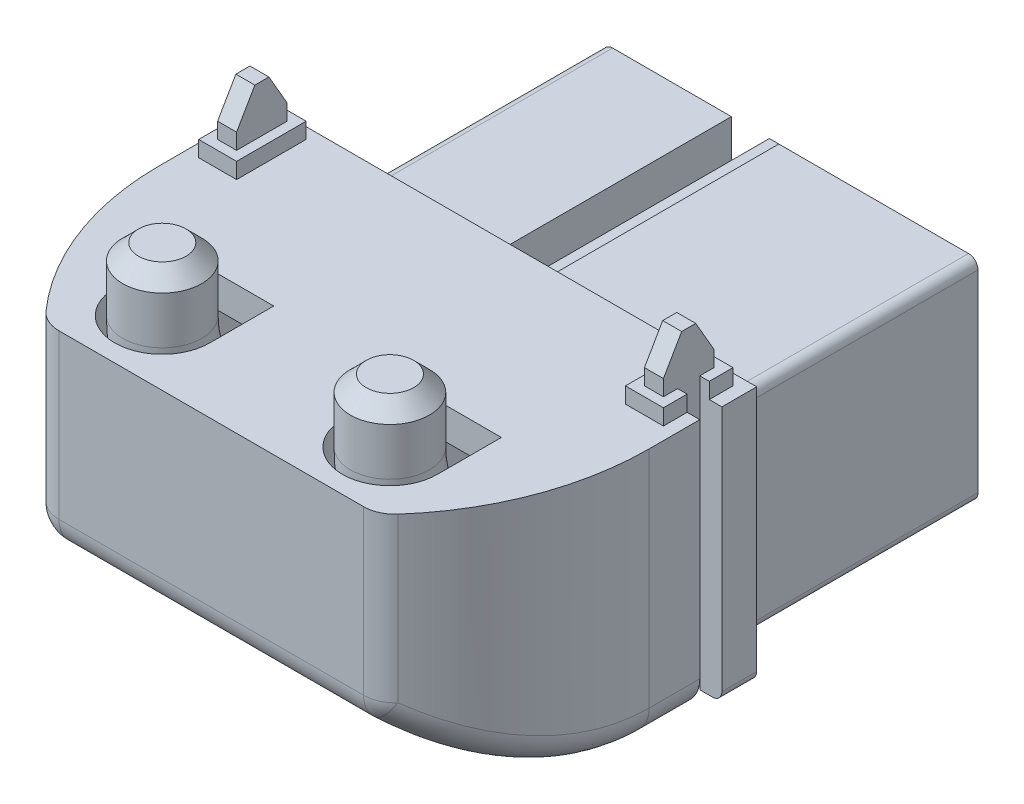
SolidWorks part; units mm, degrees
ref_plane "Спереди" through (0, 0, 0) normal (0, 0, 1) x (1, 0, 0)
ref_plane "Сверху" through (0, 0, 0) normal (0, 1, 0) x (1, 0, 0)
ref_plane "Справа" through (0, 0, 0) normal (1, 0, 0) x (0, 0, -1)
sketch "Эскиз1" plane through (0, 0, 0) normal (0, 0, 1) x (1, 0, 0)
  line L0 (-7.75, -1.2216) -> (-4.9216, -4.05)
  line L1 (-7.75, 4.05) -> (7.75, 4.05)
  line L2 (-7.75, 4.05) -> (-7.75, -4.05)
  line L3 (-7.75, -4.05) -> (7.75, -4.05)
  line L4 (7.75, 4.05) -> (7.75, -4.05)
  line L5 (-7.75, 4.05) -> (7.75, -4.05) construction
  line L6 (-7.75, -4.05) -> (7.75, 4.05) construction
  line L7 (0, 0) -> (7.75, 0) construction
  line L8 (-7.75, 1.2216) -> (-4.9216, 4.05)
  point P0 (0, 0)
  dimension "D1" = 8.1
  dimension "D2" = 15.5
  dimension "D3" = 45
  dimension "D4" = 4
extrude "Бобышка-Вытянуть1" add sketch "Эскиз1" along normal blind 11.1 contours L8 L2 L0 L3 L4 L1
sketch "Эскиз2" plane through (0, 0, 0) normal (0, 0, -1) x (-1, 0, 0)
  line L6 (7.05, 0.9316) -> (4.6316, 3.35)
  line L7 (7.05, 0.9316) -> (4.6316, 3.35)
  line L8 (4.6316, -3.35) -> (7.05, -0.9316)
  line L9 (4.6316, -3.35) -> (7.05, -0.9316)
  line L12 (-7.05, -3.35) -> (4.6316, -3.35)
  line L13 (7.05, -0.9316) -> (7.05, 0.9316)
  line L14 (4.6316, 3.35) -> (-7.05, 3.35)
  line L16 (-7.05, 3.35) -> (-7.05, -3.35)
  line L18 (-7.05, -3.35) -> (4.6316, -3.35)
  line L19 (7.05, -0.9316) -> (7.05, 0.9316)
  line L20 (4.6316, 3.35) -> (-7.05, 3.35)
  line L22 (-7.05, 3.35) -> (-7.05, -3.35)
  dimension "D1" = 0.7
extrude "Вырез-Вытянуть1" cut sketch "Эскиз2" against normal blind 7.7
sketch "Эскиз13" plane through (0, 0, 0) normal (0, 0, -1) x (-1, 0, 0)
  line L0 (0, 0) -> (0, 1.988) construction
  circle A0 centre (-3.6, 0) radius 2.175
  circle A1 centre (3.6, 0) radius 2.175
  dimension "D1" = 4.35
  dimension "D2" = 7.2
extrude "Вырез-Вытянуть9" cut sketch "Эскиз13" against normal blind 7.7
ref_plane "Плоскость1" through (0, 0, 1.5) normal (0, 0, -1) x (-1, 0, 0)
sketch "Эскиз3" plane through (0, 0, 1.5) normal (0, 0, -1) x (-1, 0, 0)
  line L1 (-7.05, 3.35) -> (4.6316, 3.35) construction
  line L2 (-0.75, 2.15) -> (0.75, 2.15)
  line L3 (-0.75, 2.15) -> (-0.75, 3.35)
  line L4 (-0.75, 3.35) -> (0.75, 3.35)
  line L5 (0.75, 2.15) -> (0.75, 3.35)
  line L6 (-0.75, 2.15) -> (0.75, 3.35) construction
  line L7 (-0.75, 3.35) -> (0.75, 2.15) construction
  point P1 (0, 2.75)
  dimension "D1" = 1.2
  dimension "D2" = 1.5
extrude "Вырез-Вытянуть10" cut sketch "Эскиз3" against normal up to surface and the other way up to surface up to face at (-1.5439, 0, 7.7) other way up to face at (1.425, 0, 0)
sketch "Эскиз14" plane through (0, 0, 0) normal (0, 0, -1) x (-1, 0, 0)
  line L1 (-0.75, 2.15) -> (0.75, 2.15)
  line L2 (-0.75, 2.15) -> (-0.75, -1.85)
  line L3 (-0.75, -1.85) -> (0.75, -1.85)
  line L4 (0.75, 2.15) -> (0.75, -1.85)
  dimension "D1" = 4
  dimension "D2" = 1.5
extrude "Бобышка-Вытянуть5" add sketch "Эскиз14" along normal blind 1.2
sketch "Эскиз5" plane through (0, 0, 7.7) normal (0, 0, -1) x (-1, 0, 0)
  line L0 (0, 0) -> (0, -2.5029) construction
  circle A0 centre (3.6, 0) radius 2.175
  circle A1 centre (-3.6, 0) radius 2.175
  dimension "D1" = 4.35
  dimension "D2" = 7.2
extrude "Бобышка-Вытянуть3" add sketch "Эскиз5" along normal offset from surface (6.5 mm away) 1.2 up to face at (-1.425, 0, 0)
sketch "Эскиз10" plane through (0, 0, 1.2) normal (0, 0, -1) x (-1, 0, 0)
  line L0 (0, 0) -> (0, 1.4291) construction
  circle A8 centre (-3.6, 0) radius 2.15
  circle A9 centre (3.6, 0) radius 2.15
  dimension "D1" = 4.3
extrude "Вырез-Вытянуть7" cut sketch "Эскиз10" against normal up to surface (6.5 mm away) up to face at (-0.9263, 1.1, 7.7)
sketch "Эскиз16" plane through (0, 0, 11.1) normal (0, 0, 1) x (1, 0, 0)
  line L0 (0, 0) -> (0, -1.8762) construction
  circle A0 centre (3.6, 0) radius 1.25
  circle A1 centre (-3.6, 0) radius 1.25
  dimension "D1" = 2.5
  dimension "D2" = 7.2
sketch "Эскиз17" plane through (0, 0, 0) normal (1, 0, 0) x (0, 0, -1)
  line L0 (-11.1, 0) -> (-11.1, 4.05) construction
  line L2 (-11.1, 4.05) -> (-15.15, 4.05) construction
  arc A0 (-15.15, 4.05) -> (-11.1, 0) centre (-11.1, 4.05) ccw
  point P7 (-11.1, 4.05)
  point P9 (-10.9589, 0)
  dimension "D1" = 4.05
sweep "По траектории1" add profiles "Эскиз16" path "Эскиз17"
sketch "Эскиз18" plane through (0, 4.05, 0) normal (0, 1, 0) x (1, 0, 0)
  circle A0 centre (3.6, -15.15) radius 1.25 construction
  circle A1 centre (-3.6, -15.15) radius 1.25 construction
  circle A2 centre (3.6, -15.15) radius 1.25
  circle A3 centre (-3.6, -15.15) radius 1.25
extrude "Бобышка-Вытянуть7" add sketch "Эскиз18" along normal blind 2
sketch "Эскиз19" plane through (0, 4.05, 0) normal (0, 1, 0) x (1, 0, 0)
  line L0 (-4.9216, -11.1) -> (7.75, -11.1) construction
  line L1 (7.75, -11.1) -> (-7.75, -11.1)
  line L2 (7.75, -11.1) -> (7.75, -17.2)
  line L3 (7.75, -17.2) -> (-7.75, -17.2)
  line L4 (-7.75, -11.1) -> (-7.75, -17.2)
  line L6 (-4.6316, 0) -> (-0.75, 0) construction
  line L7 (7.75, -11.1) -> (7.75, -7.7) construction
  line L8 (0, -17.2) -> (0, -8.2437) construction
  line L9 (5.1, -15.15) -> (5.1, -11.1)
  line L10 (2.1, -15.15) -> (2.1, -11.1)
  line L11 (-2.1, -15.15) -> (-2.1, -11.1)
  line L12 (-5.1, -15.15) -> (-5.1, -11.1)
  line L13 (7.75, -7.7) -> (-7.75, -7.7)
  line L14 (7.75, -7.7) -> (7.75, -11.1)
  line L15 (7.75, -11.1) -> (-7.75, -11.1)
  line L16 (-7.75, -7.7) -> (-7.75, -11.1)
  arc A0 (7.75, -11.1) -> (5.25, -17.2) centre (-0.942, -11.1) cw
  arc A1 (-7.75, -11.1) -> (-5.25, -17.2) centre (0.942, -11.1) ccw
  arc A2 (2.1, -15.15) -> (5.1, -15.15) centre (3.6, -15.15) ccw
  arc A3 (-2.1, -15.15) -> (-5.1, -15.15) centre (-3.6, -15.15) cw
  point P12 (-7.75, -11.1)
  dimension "D2" = 2.5
  dimension "D3" = 3
  dimension "D1" = 17.2
extrude "Бобышка-Вытянуть8" add sketch "Эскиз19" against normal up to surface (8.1 mm away) up to face at (1.4142, -4.05, 9.4)
sketch "Эскиз20" plane through (0, -4.05, 0) normal (0, -1, 0) x (1, 0, 0)
  line L4 (-7.75, 7.7) -> (7.75, 7.7)
  line L5 (7.75, 7.7) -> (7.75, 11.1)
  line L6 (5.25, 17.2) -> (-5.25, 17.2)
  line L7 (-7.75, 11.1) -> (-7.75, 7.7)
  line L8 (-7.75, 7.7) -> (7.75, 7.7)
  line L9 (7.75, 7.7) -> (7.75, 11.1)
  line L10 (5.25, 17.2) -> (-5.25, 17.2)
  line L12 (-7.75, 11.1) -> (-7.75, 7.7)
  arc A2 (7.75, 11.1) -> (5.25, 17.2) centre (-0.942, 11.1) ccw
  arc A3 (-5.25, 17.2) -> (-7.75, 11.1) centre (0.942, 11.1) ccw
  arc A4 (7.75, 11.1) -> (5.25, 17.2) centre (-0.942, 11.1) ccw
  arc A5 (-5.25, 17.2) -> (-7.75, 11.1) centre (0.942, 11.1) ccw
  dimension "D1" = 0
extrude "Бобышка-Вытянуть9" add sketch "Эскиз20" against normal blind 2.1
sketch "Эскиз21" plane through (0, 4.05, 0) normal (0, 1, 0) x (1, 0, 0)
  line L0 (-5.1, -15.15) -> (-5.1, -11.1) construction
  line L1 (5.1, -11.1) -> (-5.1, -11.1)
  line L2 (5.1, -11.1) -> (5.1, -13.125)
  line L3 (5.1, -13.125) -> (-5.1, -13.125)
  line L4 (-5.1, -11.1) -> (-5.1, -13.125)
extrude "Бобышка-Вытянуть12" add sketch "Эскиз21" against normal blind 1
sketch "Эскиз22" plane through (0, 4.05, 0) normal (0, 1, 0) x (1, 0, 0)
  line L0 (0, -9.1897) -> (0, 0) construction
  line L1 (-7.05, -8.35) -> (-6.45, -8.35)
  line L2 (-7.05, -8.35) -> (-7.05, -9.95)
  line L3 (-7.05, -9.95) -> (-6.45, -9.95)
  line L4 (-6.45, -8.35) -> (-6.45, -9.95)
  line L5 (-7.05, -8.35) -> (-6.45, -9.95) construction
  line L6 (-7.05, -9.95) -> (-6.45, -8.35) construction
  line L11 (7.05, -9.95) -> (6.45, -8.35) construction
  line L12 (7.05, -8.35) -> (6.45, -9.95) construction
  line L13 (6.45, -8.35) -> (6.45, -9.95)
  line L14 (7.05, -9.95) -> (6.45, -9.95)
  line L15 (7.05, -8.35) -> (7.05, -9.95)
  line L16 (7.05, -8.35) -> (6.45, -8.35)
  point P0 (-6.75, -9.15)
  point P12 (-3.6, -15.15)
  point P13 (6.75, -9.15)
  dimension "D1" = 1.6
  dimension "D2" = 0.6
  dimension "D3" = 6
  dimension "D4" = 13.5
extrude "Вырез-Вытянуть12" cut sketch "Эскиз22" against normal through all
sketch "Эскиз23" plane through (0, 4.05, 0) normal (0, 1, 0) x (1, 0, 0)
  line L0 (-7.05, -9.15) -> (7.05, -9.15) construction
  line L1 (-7.05, -8.35) -> (-7.05, -9.95) construction
  line L2 (7.05, -9.95) -> (7.05, -8.35) construction
  line L3 (-7.75, -11.1) -> (-7.75, -7.7) construction
  line L4 (-7.75, -8.8) -> (-7.05, -8.8)
  line L5 (-7.75, -8.8) -> (-7.75, -9.5)
  line L6 (-7.75, -9.5) -> (-7.05, -9.5)
  line L7 (-7.05, -8.8) -> (-7.05, -9.5)
  line L8 (-7.75, -8.8) -> (-7.05, -9.5) construction
  line L9 (-7.75, -9.5) -> (-7.05, -8.8) construction
  line L10 (0, 0) -> (0, -11.1203) construction
  line L11 (7.75, -9.5) -> (7.05, -9.5)
  line L12 (7.05, -8.8) -> (7.05, -9.5)
  line L13 (7.75, -8.8) -> (7.05, -8.8)
  line L14 (7.75, -8.8) -> (7.75, -9.5)
  point P6 (-7.4, -9.15)
  dimension "D1" = 0.7
extrude "Вырез-Вытянуть13" cut sketch "Эскиз23" against normal through all
sketch "Эскиз24" plane through (0, 4.05, 0) normal (0, 1, 0) x (1, 0, 0)
  line L1 (-7.05, -8.35) -> (-6.45, -8.35)
  line L2 (-7.05, -8.35) -> (-7.05, -9.95)
  line L3 (-7.05, -9.95) -> (-6.45, -9.95)
  line L4 (-6.45, -8.35) -> (-6.45, -9.95)
  line L5 (6.45, -8.35) -> (7.05, -8.35)
  line L6 (6.45, -8.35) -> (6.45, -9.95)
  line L7 (6.45, -9.95) -> (7.05, -9.95)
  line L8 (7.05, -8.35) -> (7.05, -9.95)
extrude "Бобышка-Вытянуть13" add sketch "Эскиз24" along normal blind 2 and the other way offset from surface (7.6 mm away) 0.5 other way up to face at (0, -4.05, 9.9497)
sketch "Эскиз25" plane through (0, 4.05, 0) normal (0, 1, 0) x (1, 0, 0)
  line L0 (-7.05, -8.35) -> (-7.05, -8.8) construction
  line L1 (-7.35, -8.05) -> (-6.15, -8.05)
  line L2 (-7.35, -8.05) -> (-7.35, -10.25)
  line L3 (-7.35, -10.25) -> (-6.15, -10.25)
  line L4 (-6.15, -8.05) -> (-6.15, -10.25)
  line L5 (-6.45, -9.95) -> (-6.45, -8.35) construction
  line L6 (-6.45, -8.35) -> (-7.05, -8.35) construction
  line L7 (-7.05, -9.95) -> (-6.45, -9.95) construction
  line L8 (0, 0) -> (0, -8.7982) construction
  line L9 (6.15, -8.05) -> (6.15, -10.25)
  line L10 (7.35, -10.25) -> (6.15, -10.25)
  line L11 (7.35, -8.05) -> (7.35, -10.25)
  line L12 (7.35, -8.05) -> (6.15, -8.05)
  line M5 (-7.05, -9.5) -> (-7.75, -9.5)
  line M11 (7.75, -9.5) -> (7.05, -9.5)
  line M12 (7.05, -9.5) -> (7.05, -9.95)
  line M13 (7.05, -9.95) -> (6.45, -9.95)
  line M14 (6.45, -9.95) -> (6.45, -8.35)
  line M15 (6.45, -8.35) -> (7.05, -8.35)
  line M16 (7.05, -8.35) -> (7.05, -8.8)
  line M17 (7.05, -8.8) -> (7.75, -8.8)
  line M21 (-7.75, -8.8) -> (-7.05, -8.8)
  line M22 (-7.05, -8.8) -> (-7.05, -8.35)
  line M23 (-7.05, -8.35) -> (-6.45, -8.35)
  line M24 (-6.45, -8.35) -> (-6.45, -9.95)
  line M25 (-6.45, -9.95) -> (-7.05, -9.95)
  line M26 (-7.05, -9.95) -> (-7.05, -9.5)
  dimension "D1" = 0.3
  dimension "D2" = 0.3
  dimension "D3" = 0.3
  dimension "D4" = 0.3
extrude "Бобышка-Вытянуть14" add sketch "Эскиз25" along normal blind 0.5 contours L4 L1 L2 L3 M21 M22 M23 M24 M25 M26 M5 | L11 L12 L9 L10 M11 M12 M13 M14 M15 M16 M17
chamfer "Фаска2" distance 1 angle 30 4 edges at (6.75, 6.05, 8.35) (6.75, 6.05, 9.95) (-6.75, 6.05, 9.95) (-6.75, 6.05, 8.35)
chamfer "Фаска3" distance 0.5 angle 45 2 edges at (3.6, 6.05, 16.4) (-3.6, 6.05, 16.4)
sketch "Эскиз26" plane through (0, -4.05, 0) normal (0, -1, 0) x (1, 0, 0)
  line L0 (-6.45, 9.95) -> (-7.05, 9.95) construction
  line L1 (4.95, 8.35) -> (-4.95, 8.35)
  line L2 (4.95, 8.35) -> (4.95, 9.95)
  line L3 (4.95, 9.95) -> (-4.95, 9.95)
  line L4 (-4.95, 8.35) -> (-4.95, 9.95)
  line L5 (7.05, 8.35) -> (6.45, 8.35) construction
  line L6 (6.45, 8.35) -> (6.45, 9.95) construction
  line L7 (-6.45, 8.35) -> (-6.45, 9.95) construction
  dimension "D1" = 1.5
  dimension "D2" = 1.5
extrude "Вырез-Вытянуть14" cut sketch "Эскиз26" against normal blind 0.7
fillet "Скругление4" radius 0.3 12 edges at (4.95, -3.7, 9.95) (4.95, -3.7, 8.35) (-4.95, -3.7, 9.95) (-4.95, -3.7, 8.35) (-7.75, -4.05, 8.25) (-4.6316, 3.35, 3.85) (-7.05, 0.9316, 3.85) (-7.05, -0.9316, 3.85) (7.05, 3.35, 3.85) (-4.6316, -3.35, 3.85) (7.05, -3.35, 3.85) (7.75, -4.05, 8.25)
sketch "Эскиз27" plane through (0, 0, 0) normal (1, 0, 0) x (0, 0, -1)
  line L0 (-11.1, -4.05) -> (-17.2, -4.05)
  line L1 (-17.2, -4.05) -> (-17.2, -1.55)
  line L2 (-17.2, -4.05) -> (-17.2, 4.05) construction
  line L3 (-11.1, -4.05) -> (-9.5, -4.05) construction
  arc A0 (-17.2, -1.55) -> (-11.1, -4.05) centre (-11.1, 4.642) ccw
  dimension "D1" = 2.5
extrude "Вырез-Вытянуть15" cut sketch "Эскиз27" against normal through all both and the other way through all
fillet "Скругление5" radius 1 7 edges at (7.75, -4.05, 10.3) (-7.75, -4.05, 10.3) (5.25, 1.25, 17.2) (-5.25, 1.25, 17.2) (7.1008, -3.4008, 14.3962) (-7.1008, -3.4008, 14.3962) (0, -1.55, 17.2)
